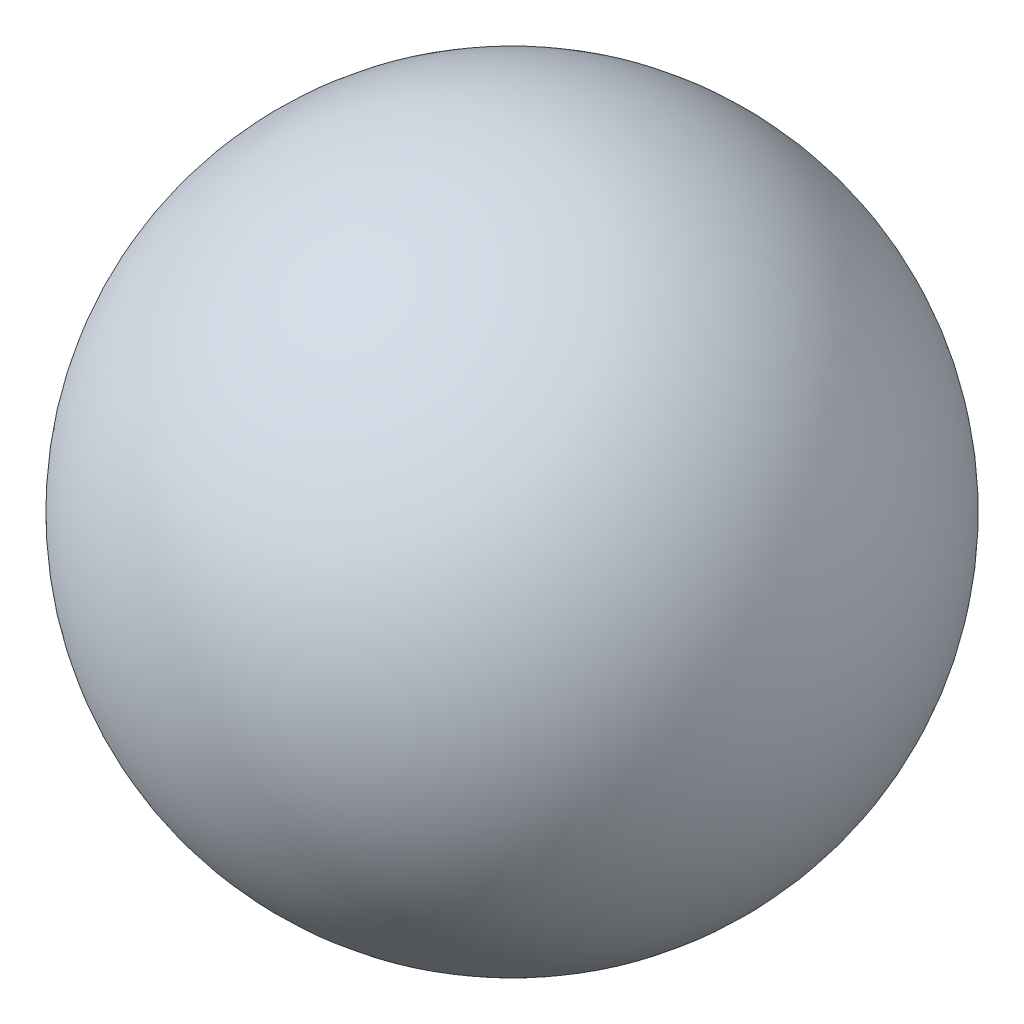
SolidWorks part; units mm, degrees
ref_plane "Front Plane" through (0, 0, 0) normal (0, 0, 1) x (1, 0, 0)
ref_plane "Top Plane" through (0, 0, 0) normal (0, 1, 0) x (1, 0, 0)
ref_plane "Right Plane" through (0, 0, 0) normal (1, 0, 0) x (0, 0, -1)
sketch "Sketch1" plane through (0, 0, 0) normal (0, 0, 1) x (1, 0, 0)
  line L0 (0, 4) -> (0, -4)
  arc A0 (0, -4) -> (0, 4) centre (0, 0) ccw
revolve "Revolve1" add sketch "Sketch1" angle 360 about L0
